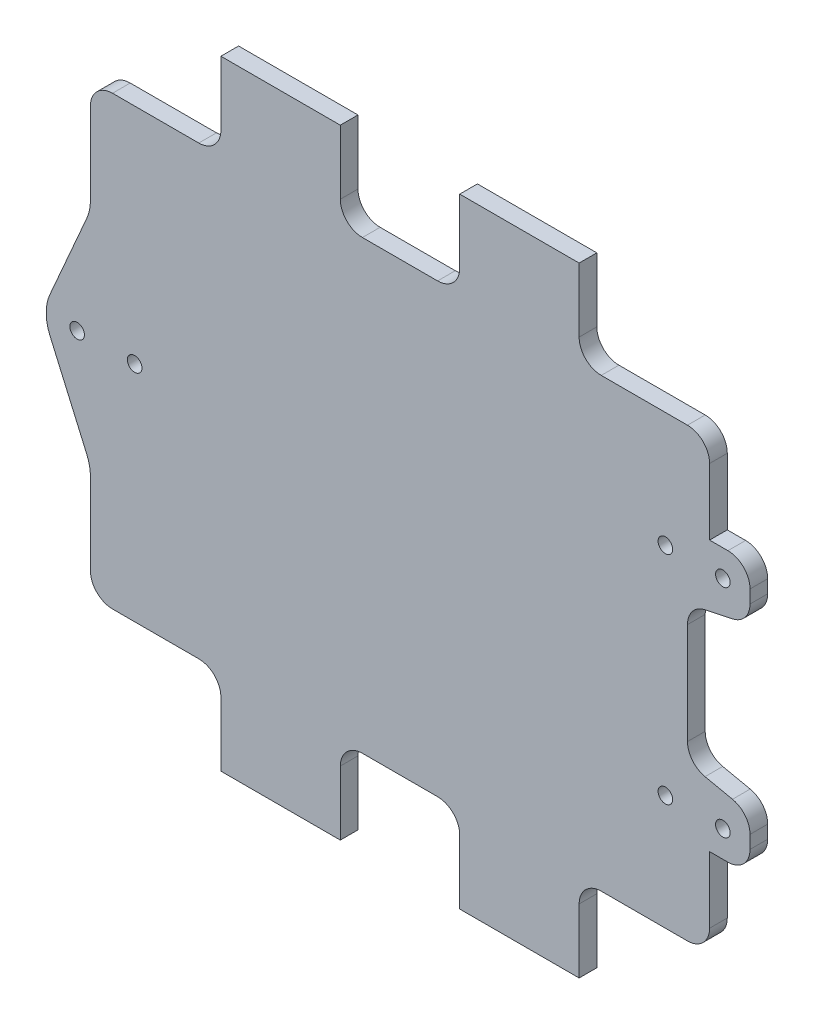
SolidWorks part; units mm, degrees
material "Ceramic Porcelain"
ref_plane "Front Plane" through (0, 0, 0) normal (0, 0, 1) x (1, 0, 0)
ref_plane "Top Plane" through (0, 0, 0) normal (0, 1, 0) x (1, 0, 0)
ref_plane "Right Plane" through (0, 0, 0) normal (1, 0, 0) x (0, 0, -1)
sketch "Sketch1" plane through (0, 0, 0) normal (0, 0, 1) x (1, 0, 0)
  line L0 (135, 70) -> (-19.1725, 70) construction
  line L1 (0, 0) -> (135, 0)
  line L2 (0, 0) -> (0, 42.9273)
  line L3 (0, 140) -> (135, 140)
  line L4 (135, 0) -> (135, 140)
  line L5 (-9.164, 74.0025) -> (-0.836, 93.0702)
  line L6 (-9.164, 65.9975) -> (-0.836, 46.9298)
  line L7 (0, 97.0727) -> (0, 140)
  line L8 (0, 97.0727) -> (0, 42.9273) construction
  arc A0 (-9.164, 65.9975) -> (-9.164, 74.0025) centre (0, 70) cw
  arc A1 (-0.836, 93.0702) -> (0, 97.0727) centre (-10, 97.0727) ccw
  arc A2 (-0.836, 46.9298) -> (0, 42.9273) centre (-10, 42.9273) cw
  point P14 (0, 94.9841)
  dimension "D2" = 10
  dimension "D3" = 10
  dimension "D4" = 10
  dimension "D1" = 140
  dimension "D5" = 135
extrude "Boss-Extrude1" add sketch "Sketch1" along normal blind 4
sketch "Sketch2" plane through (0, 0, 4) normal (0, 0, 1) x (1, 0, 0)
  line L0 (0, 42.9273) -> (0, 0) construction
  line L1 (5, 5) -> (27, 5)
  line L2 (5, 5) -> (5, 27)
  line L3 (5, 27) -> (27, 27)
  line L4 (27, 5) -> (27, 27)
  line L5 (0, 0) -> (135, 0) construction
  dimension "D1" = 22
  dimension "D2" = 5
  dimension "D3" = 5
extrude "Cut-Extrude2" [suppressed] cut sketch "Sketch2" against normal blind 3
chamfer "Chamfer1" [suppressed] distance 3 angle 15
fillet "Fillet3" [suppressed] radius 1
fillet "Fillet4" [suppressed] radius 1
pattern_linear "LPattern1" [suppressed] count 5 spacing 27 count 5 spacing 27
sketch "Sketch3" plane through (0, 0, 4) normal (0, 0, 1) x (1, 0, 0)
  line L0 (0, 0) -> (135, 0) construction
  line L1 (0, 0) -> (29.5, 0)
  line L2 (0, 0) -> (0, 19.5)
  line L3 (0, 19.5) -> (29.5, 19.5)
  line L4 (29.5, 0) -> (29.5, 19.5)
  line L5 (56.5, 0) -> (83.5, 0)
  line L6 (56.5, 0) -> (56.5, 19.5)
  line L7 (56.5, 19.5) -> (83.5, 19.5)
  line L8 (83.5, 0) -> (83.5, 19.5)
  line L9 (70, 0) -> (70, 140) construction
  line L10 (140, 140) -> (110.5, 140)
  line L11 (140, 140) -> (140, 120.5)
  line L15 (110.5, 0) -> (110.5, 19.5)
  line L16 (140, 19.5) -> (110.5, 19.5)
  line L17 (140, 0) -> (140, 19.5)
  line L18 (140, 0) -> (110.5, 0)
  line L19 (140, 120.5) -> (110.5, 120.5)
  line L20 (110.5, 140) -> (110.5, 120.5)
  line L21 (29.5, 140) -> (29.5, 120.5)
  line L22 (0, 120.5) -> (29.5, 120.5)
  line L23 (0, 140) -> (0, 120.5)
  line L24 (0, 140) -> (29.5, 140)
  line L25 (0, 0) -> (140, 140) construction
  line L31 (83.5, 140) -> (83.5, 120.5)
  line L32 (56.5, 120.5) -> (83.5, 120.5)
  line L33 (56.5, 140) -> (56.5, 120.5)
  line L34 (56.5, 140) -> (83.5, 140)
  dimension "D1" = 19.5
  dimension "D2" = 56.5
  dimension "D3" = 27
  dimension "D4" = 29.5
extrude "Cut-Extrude3" cut sketch "Sketch3" against normal through all
sketch "Sketch9" plane through (0, 0, 0) normal (0, 0, -1) x (-1, 0, 0)
  line L0 (-140, 100.5) -> (-149.1421, 100.5)
  line L1 (-149.1421, 100.5) -> (-149.1421, 88.5)
  line L2 (-149.1421, 88.5) -> (-135, 85.5)
  line L3 (-135, 19.5) -> (-135, 120.5) construction
  line L4 (-135, 70) -> (-101.7414, 70) construction
  line L5 (-135, 105.5) -> (-135, 85.5)
  line L6 (-140, 19.5) -> (-140, 39.5)
  line L7 (-135, 19.5) -> (-135, 34.5)
  line L8 (-135, 19.5) -> (-140, 19.5)
  line L9 (-135, 34.5) -> (-135, 54.5)
  line L10 (-110.5, 120.5) -> (-135, 120.5) construction
  line L11 (-149.1421, 51.5) -> (-135, 54.5)
  line L12 (-135, 120.5) -> (-140, 120.5)
  line L13 (-135, 120.5) -> (-135, 105.5)
  line L14 (-149.1421, 39.5) -> (-149.1421, 51.5)
  line L15 (-140, 120.5) -> (-140, 100.5)
  line L16 (-140, 39.5) -> (-149.1421, 39.5)
  dimension "D1" = 15
  dimension "D2" = 12
  dimension "D3" = 15
  dimension "D4" = 20
  dimension "D5" = 5
extrude "Boss-Extrude2" add sketch "Sketch9" against normal up to surface (4 mm away) up to face at (52.6761, 70, 4)
fillet "Fillet5" radius 5 6 edges at (149.1421, 88.5, 2) (149.1421, 100.5, 2) (149.1421, 39.5, 2) (149.1421, 51.5, 2) (135, 54.5, 2)
sketch "Sketch10" [suppressed] plane through (0, 0, 6) normal (0, 0, 1) x (1, 0, 0)
  line L0 (127.2327, 102) -> (127.2327, 108.7673)
  line L1 (112.2327, 108.7673) -> (135.7673, 108.7673) construction
  line L2 (127.2327, 108.7673) -> (135.7673, 108.7673)
  line L3 (134, 95.2327) -> (135.7673, 95.2327)
  line L4 (135.7673, 108.7673) -> (135.7673, 85.2327) construction
  line L5 (135.7673, 95.2327) -> (135.7673, 108.7673)
  line L6 (127.2327, 38) -> (127.2327, 31.2327)
  line L7 (135.7673, 31.2327) -> (112.2327, 31.2327) construction
  line L8 (127.2327, 31.2327) -> (135.7673, 31.2327)
  line L9 (135.7673, 31.2327) -> (135.7673, 44.7673)
  line L10 (135.7673, 54.7673) -> (135.7673, 31.2327) construction
  line L11 (135.7673, 44.7673) -> (134, 44.7673)
  line L12 (4.2327, 74.1422) -> (6, 74.1422)
  line L13 (4.2327, 58.2327) -> (4.2327, 81.7673) construction
  line L14 (4.2327, 74.1422) -> (4.2327, 65.8578)
  line L15 (4.2327, 65.8578) -> (6, 65.8578)
  arc A1 (134, 44.7673) -> (127.2327, 38) centre (134, 38) ccw
  arc A2 (6, 65.8578) -> (6, 74.1422) centre (6, 70) ccw
  arc A3 (127.2327, 102) -> (134, 95.2327) centre (134, 102) ccw
extrude "Boss-Extrude3" [suppressed] add sketch "Sketch10" against normal up to surface (3 mm away)
hole_wizard "CSK for M3 Flat Head Machine Screw1" positions "Sketch6" profile "Sketch5" countersink size "M3" standard "Ansi Metric" end condition through all
sketch "Sketch6" plane through (0, 0, 0) normal (0, 0, -1) x (-1, 0, 0)
  line L0 (3.5733, 70) -> (-135, 70) construction
  line L5 (-130, 94.5) -> (-130, 45.5) construction
  line L6 (-135, 58.5506) -> (-135, 81.4494) construction
  line L8 (-140, 100.5) -> (-140, 120.5) construction
  point P0 (-10, 70)
  point P20 (-130, 94.5)
  point P22 (-130, 45.5)
  dimension "D1" = 10
  dimension "D2" = 10
  dimension "D3" = 24.5
  dimension "D4" = 49
sketch "Sketch5" plane through (10, 70, 0) normal (1, 0, 0) x (0, 1, 0)
  line L0 (0, 0) -> (0, 4)
  line L1 (0, 4) -> (1.65, 4)
  line L2 (1.65, 4) -> (1.65, 1.35)
  line L3 (1.65, 1.35) -> (3, 0)
  line L5 (3, 0) -> (0, 0)
  line L6 (-1.65, 1.35) -> (-3, 0) construction
  line L11 (0, -6.35) -> (0, 107.95) construction
  dimension "Thru Hole Dia." = 3.3
  dimension "Thru Hole Depth" = 4
  dimension "Near C'Sink Dia." = 6
  dimension "Near C'Sink Angle" = 90
sketch "Sketch8" plane through (0, 0, 0) normal (0, 0, -1) x (-1, 0, 0)
  line L0 (-135, 70) -> (10, 70) construction
  line L2 (-130, 94.5) -> (-143, 94.5) construction
  line L3 (-130, 45.5) -> (-143, 45.5) construction
  line L4 (-135, 58.5506) -> (-135, 81.4494) construction
  arc A0 (9.164, 65.9975) -> (9.164, 74.0025) centre (0, 70) ccw construction
  circle A1 centre (3, 70) radius 1.65
  circle A2 centre (-10, 70) radius 1.65 construction
  circle A3 centre (-143, 94.5) radius 1.65
  circle A4 centre (-143, 45.5) radius 1.65
  dimension "D1" = 13
  dimension "D2" = 3.3
  dimension "D3" = 13
extrude "Cut-Extrude4" cut sketch "Sketch8" against normal through all
fillet "Fillet6" radius 5 12 edges at (29.5, 19.5, 2) (83.5, 19.5, 2) (56.5, 19.5, 2) (110.5, 19.5, 2) (29.5, 120.5, 2) (83.5, 120.5, 2) (56.5, 120.5, 2) (110.5, 120.5, 2) (0, 120.5, 2) (0, 19.5, 2) (140, 19.5, 2) (140, 120.5, 2)
sketch "Sketch11" plane through (0, 0, 4) normal (0, 0, 1) x (1, 0, 0)
  line L0 (135, 70) -> (-10, 70) construction
  line L1 (135, 58.5506) -> (135, 81.4494) construction
  line L2 (110.5872, 104.7584) -> (5.6009, 104.7584)
  line L3 (5.6009, 104.7584) -> (18.3195, 74.9275)
  line L4 (18.3195, 74.9275) -> (110.5872, 104.7584)
  line L5 (117.0488, 98.8234) -> (43.1382, 74.9275)
  line L6 (43.1382, 74.9275) -> (127.237, 74.9275)
  line L7 (127.237, 74.9275) -> (117.0488, 98.8234)
  line L8 (127.237, 65.0725) -> (117.0488, 41.1766)
  line L9 (43.1382, 65.0725) -> (127.237, 65.0725)
  line L10 (117.0488, 41.1766) -> (43.1382, 65.0725)
  line L11 (18.3195, 65.0725) -> (110.5872, 35.2416)
  line L12 (5.6009, 35.2416) -> (18.3195, 65.0725)
  line L13 (110.5872, 35.2416) -> (5.6009, 35.2416)
  arc A0 (-9.164, 74.0025) -> (-9.164, 65.9975) centre (0, 70) ccw construction
extrude "Cut-Extrude5" [suppressed] cut sketch "Sketch11" against normal offset from surface (3 mm away) 1
chamfer "Chamfer2" [suppressed] distance 3 angle 5
fillet "Fillet7" [suppressed] radius 1
